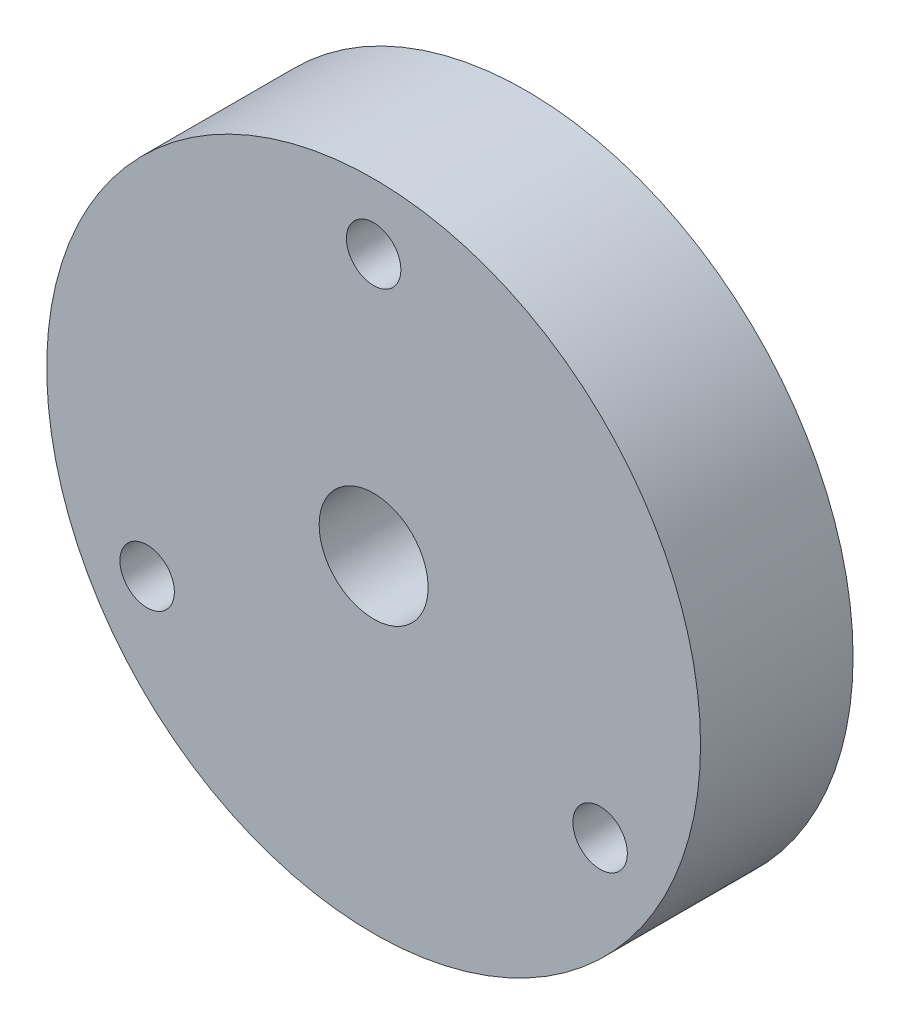
SolidWorks part; units mm, degrees
ref_plane "Front Plane" through (0, 0, 0) normal (0, 0, 1) x (1, 0, 0)
ref_plane "Top Plane" through (0, 0, 0) normal (0, 1, 0) x (1, 0, 0)
ref_plane "Right Plane" through (0, 0, 0) normal (1, 0, 0) x (0, 0, -1)
sketch "Sketch1" plane through (0, 0, 0) normal (0, 0, 1) x (1, 0, 0)
  circle A0 centre (0, 0) radius 15
  dimension "D1" = 30
extrude "Boss-Extrude2" add sketch "Sketch1" along normal blind 7
sketch "Sketch2" plane through (0, 0, 0) normal (0, 0, -1) x (-1, 0, 0)
  circle A0 centre (0, 0) radius 2.5
extrude "Cut-Extrude1" cut sketch "Sketch2" against normal blind 7
sketch "Sketch3" plane through (0, 0, 7) normal (0, 0, 1) x (1, 0, 0)
  circle A0 centre (0, 12) radius 1.25
  circle A1 centre (10.3923, -6) radius 1.25
  circle A2 centre (-10.3923, -6) radius 1.25
extrude "Cut-Extrude2" cut sketch "Sketch3" against normal through all
